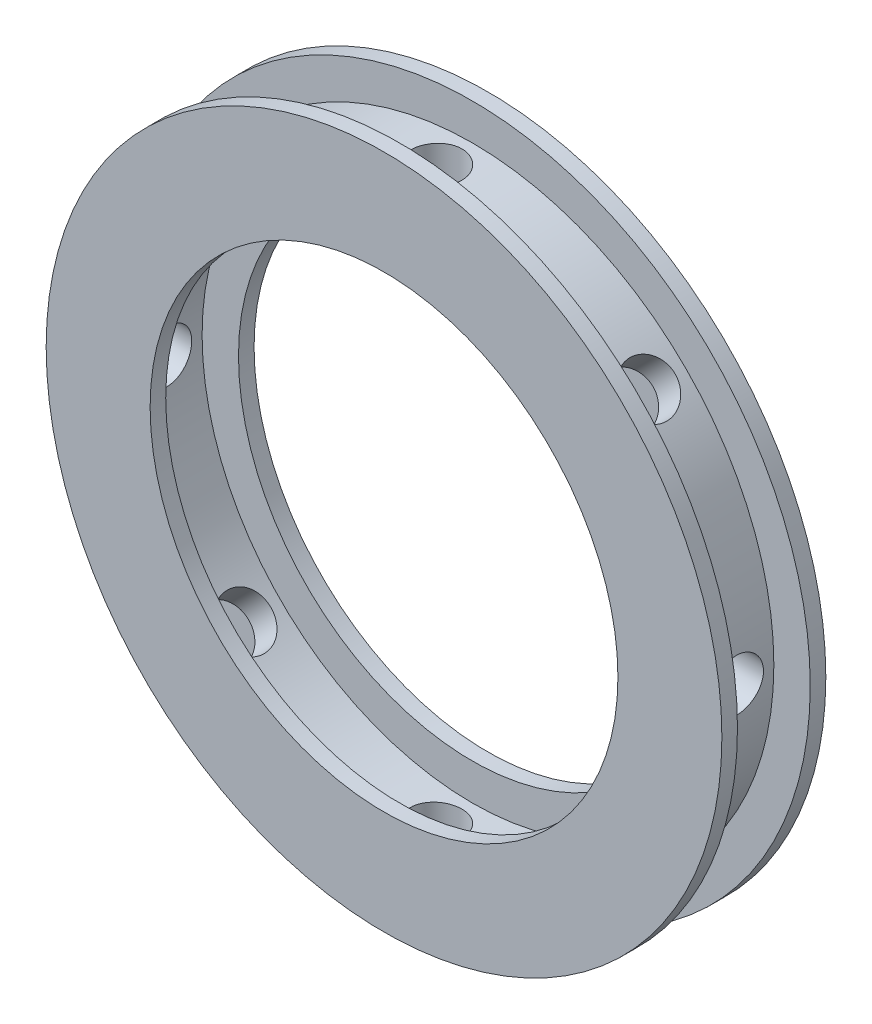
SolidWorks part; units mm, degrees
material "Cast Alloy Steel"
ref_plane "Front Plane" through (0, 0, 0) normal (0, 0, 1) x (1, 0, 0)
ref_plane "Top Plane" through (0, 0, 0) normal (0, 1, 0) x (1, 0, 0)
ref_plane "Right Plane" through (0, 0, 0) normal (1, 0, 0) x (0, 0, -1)
sketch "Sketch1" plane through (0, 0, 0) normal (1, 0, 0) x (0, 0, -1)
  line L0 (0, 0) -> (-28.6913, 0) construction
  line L1 (0, 0) -> (0, 31.7848) construction
  line L2 (5, 32.5) -> (5, 22.5)
  line L3 (-3.5, 32.5) -> (-5, 32.5)
  line L4 (-3.5, 32.5) -> (-3.5, 29)
  line L5 (-3.5, 22.5) -> (-5, 22.5)
  line L6 (-5, 32.5) -> (-5, 22.5)
  line L7 (3.5, 22.5) -> (5, 22.5)
  line L8 (3.5, 32.5) -> (3.5, 29)
  line L9 (3.5, 32.5) -> (5, 32.5)
  line L10 (-3.5, 26) -> (-3.5, 22.5)
  line L11 (-3.5, 29) -> (3.5, 29)
  line L13 (-3.5, 26) -> (3.5, 26)
  line L15 (3.5, 26) -> (3.5, 22.5)
  dimension "D1" = 1.5
  dimension "D2" = 45
  dimension "D3" = 65
  dimension "D4" = 7
  dimension "D5" = 52
  dimension "D6" = 58
revolve "Revolve1" add sketch "Sketch1" angle 360 about L0
sketch "Sketch2" plane through (0, 0, 0) normal (0, 1, 0) x (1, 0, 0)
  circle A0 centre (0, 0) radius 2.5
  dimension "D1" = 5
extrude "Cut-Extrude1" cut sketch "Sketch2" against normal through all
pattern_circular "CirPattern1" count 8 over 360 about axis through (0, 0, 0) along (0, 0, -1) of "Cut-Extrude1"
